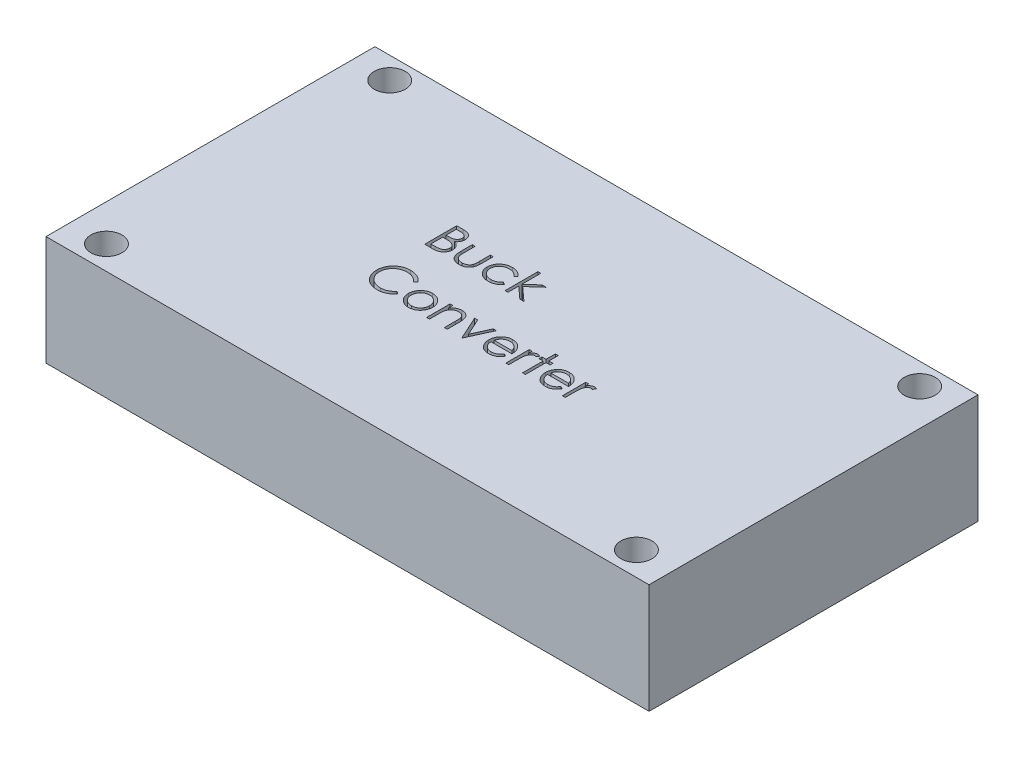
SolidWorks part; units mm, degrees
ref_plane "Front Plane" through (0, 0, 0) normal (0, 0, 1) x (1, 0, 0)
ref_plane "Top Plane" through (0, 0, 0) normal (0, 1, 0) x (1, 0, 0)
ref_plane "Right Plane" through (0, 0, 0) normal (1, 0, 0) x (0, 0, -1)
sketch "Sketch1" plane through (0, 0, 0) normal (0, 1, 0) x (1, 0, 0)
  line L1 (-33, -18) -> (33, -18)
  line L2 (-33, -18) -> (-33, 18)
  line L3 (-33, 18) -> (33, 18)
  line L4 (33, -18) -> (33, 18)
  line L5 (-33, -18) -> (33, 18) construction
  line L6 (-33, 18) -> (33, -18) construction
  point P0 (0, 0)
  dimension "D1" = 66
  dimension "D2" = 36
extrude "Boss-Extrude1" add sketch "Sketch1" along normal blind 12
sketch "Sketch2" plane through (0, 12, 0) normal (0, 1, 0) x (1, 0, 0)
  line L0 (33, 18) -> (-33, 18) construction
  line L1 (-33, 18) -> (-33, -18) construction
  line L2 (0, 18) -> (0, -18) construction
  line L3 (-33, -18) -> (33, -18) construction
  line L4 (-33, 0) -> (33, 0) construction
  line L5 (33, -18) -> (33, 18) construction
  circle A0 centre (-29, 15.6161) radius 1.7
  circle A1 centre (29, 15.6161) radius 1.7
  circle A2 centre (29, -15.3839) radius 1.7
  circle A3 centre (-29, -15.3839) radius 1.7
  text T0 "Buck \r\nConverter"
  dimension "D3" = 3.4
  dimension "D6" = 58
  dimension "D1" = 16
  dimension "D2" = 21
  dimension "D4" = 58
  dimension "D5" = 31
  dimension "D7" = 4
extrude "Cut-Extrude1" cut sketch "Sketch2" against normal through all
